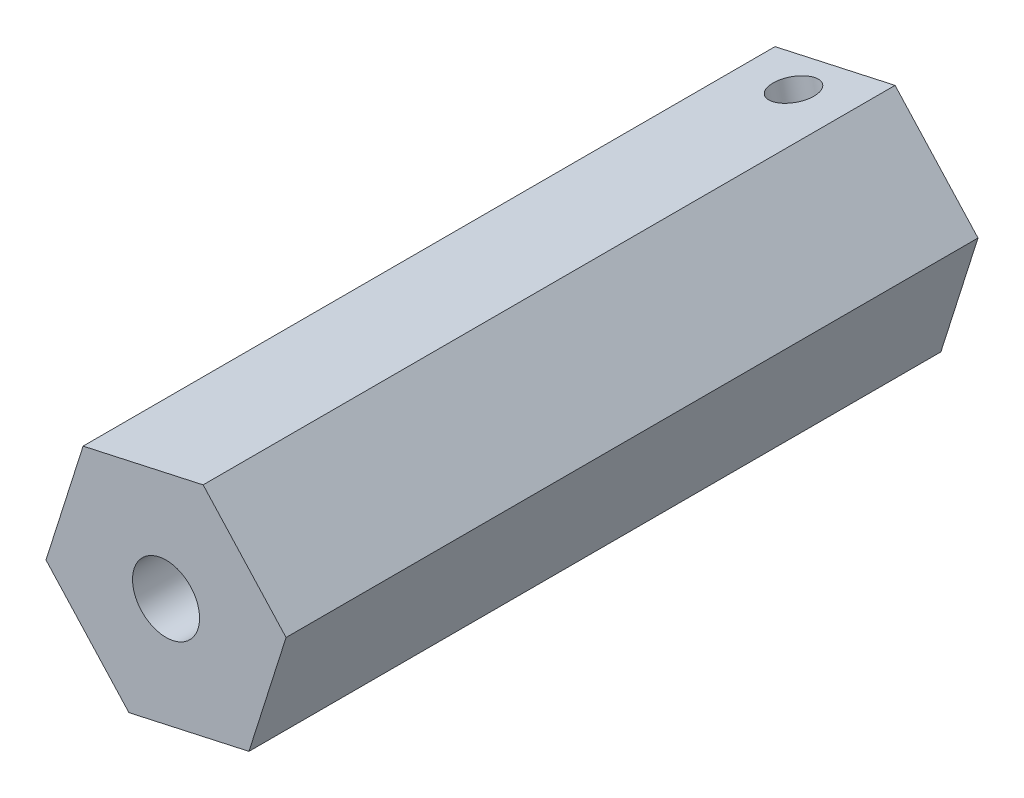
SolidWorks part; units mm, degrees
ref_plane "Front Plane" through (0, 0, 0) normal (0, 0, 1) x (1, 0, 0)
ref_plane "Top Plane" through (0, 0, 0) normal (0, 1, 0) x (1, 0, 0)
ref_plane "Right Plane" through (0, 0, 0) normal (1, 0, 0) x (0, 0, -1)
sketch "Sketch1" plane through (0, 0, 0) normal (0, 0, 1) x (1, 0, 0)
  line L1 (2.2132, 6.9903) -> (-4.9472, 5.4119)
  line L2 (-4.9472, 5.4119) -> (-7.1604, -1.5785)
  line L3 (-7.1604, -1.5785) -> (-2.2132, -6.9903)
  line L4 (-2.2132, -6.9903) -> (4.9472, -5.4119)
  line L5 (4.9472, -5.4119) -> (7.1604, 1.5785)
  line L6 (7.1604, 1.5785) -> (2.2132, 6.9903)
  circle A0 centre (0, 0) radius 6.35 construction
  circle A1 centre (0, 0) radius 2
extrude "Boss-Extrude1" add sketch "Sketch1" along normal blind 41.275
hole_wizard "M3 Tapped Hole1" positions "3DSketch1" profile "Sketch5" tap size "M3" standard "ISO"
sketch3d "3DSketch1"
  point P0 (-1.3947, 6.195, 2.4485)
cosmetic thread "Hole Thread1" parameters "D1"=4.8119, "D2"=3
sketch "Sketch5" plane through (-1.3947, 6.195, 2.4485) normal (0, 0, 1) x (-0.9766, -0.2153, 0)
  line L0 (0, 0) -> (0, 7.1011)
  line L1 (0, 7.1011) -> (1.25, 6.35)
  line L2 (1.25, 6.35) -> (1.25, 0)
  line L5 (1.25, 0) -> (0, 0)
  line L10 (0, 7.1011) -> (-1.25, 6.35) construction
  line L11 (0, -6.35) -> (0, 107.95) construction
  dimension "Tap Drill Dia." = 2.5
  dimension "Tap Drill Depth" = 6.35
  dimension "Drill Angle" = 118
